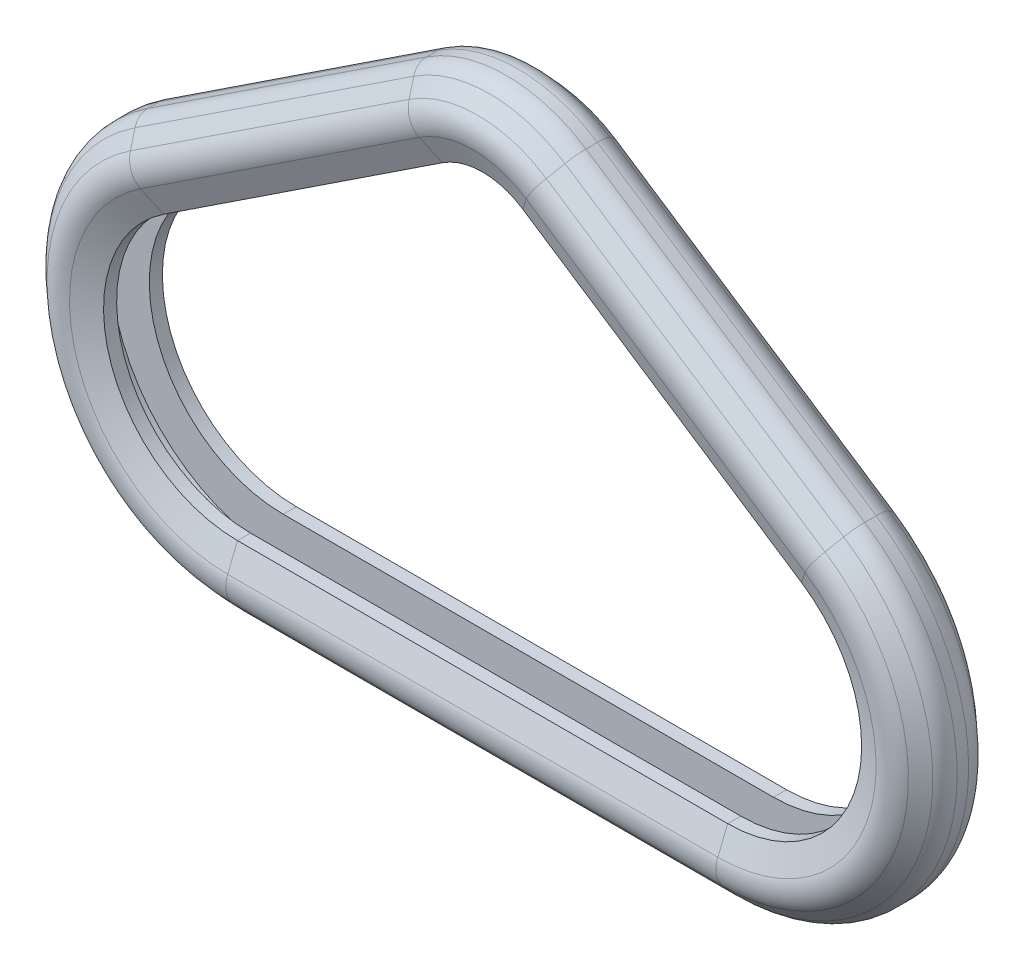
SolidWorks part; units mm, degrees
material "EPDM, dureté 60"
ref_plane "Plan de face" through (0, 0, 0) normal (0, 0, 1) x (1, 0, 0)
ref_plane "Plan de dessus" through (0, 0, 0) normal (0, 1, 0) x (1, 0, 0)
ref_plane "Plan de droite" through (0, 0, 0) normal (1, 0, 0) x (0, 0, -1)
sketch "Esquisse1" plane through (0, 0, 0) normal (0, 0, 1) x (1, 0, 0)
  line L0 (48.7921, 17.1096) -> (6.1418, 45.258)
  line L1 (-6.1418, 45.258) -> (-48.7921, 17.1096)
  line L2 (-37.5, -20.5) -> (37.5, -20.5)
  line L3 (-37.5, 0) -> (37.5, 0)
  line L4 (0, 35.9521) -> (0, 0)
  arc A0 (37.5, -20.5) -> (48.7921, 17.1096) centre (37.5, 0) ccw
  arc A1 (6.1418, 45.258) -> (-6.1418, 45.258) centre (0, 35.9521) ccw
  arc A2 (-48.7921, 17.1096) -> (-37.5, -20.5) centre (-37.5, 0) ccw
  circle B0 centre (37.5, 0) radius 20.5
  line B1 (0.1061, 35.9521) -> (0, 35.9521)
  circle B2 centre (0, 35.9521) radius 11.15
  circle B3 centre (-37.5, 0) radius 20.5
  dimension "D3" = 75
  dimension "D4" = 35.9521
sketch_block_instance "Bloc1-1"
sketch_block "Bloc1"
sketch_block_instance "Bloc2-1"
sketch_block "Bloc2" parameters "D1"=22.3
sketch_block_instance "Bloc3-1"
sketch_block "Bloc3"
other "Courroie1"
sketch "Esquisse2" plane through (0, 0, 0) normal (1, 0, 0) x (0, 0, -1)
  line L0 (-4.5, -20.5) -> (4.5, -20.5) construction
  line L1 (0, 17.1096) -> (0, -20.5) construction
  line L2 (-4.5, -20.5) -> (-2.5, -20.5)
  line L3 (4.5, -20.5) -> (2.5, -20.5)
  line L4 (-2.5, -20.5) -> (-2.5, -26.5)
  line L5 (-2.5, -26.5) -> (2.5, -26.5)
  line L6 (2.5, -26.5) -> (2.5, -20.5)
  line L7 (-12.1943, -31.5) -> (15.4694, -31.5) construction
  line L8 (-4.5, -20.5) -> (-6, -24.2081)
  line L9 (4.5, -20.5) -> (6, -24.2081)
  line L10 (-0.875, -31.5) -> (0.875, -31.5)
  line L11 (-5.2448, -28.4063) -> (-3.4588, -30.3609)
  line L12 (3.4588, -30.3609) -> (5.2448, -28.4063)
  line L13 (-2.2919, -25.7081) -> (2.2919, -25.7081) construction
  arc A0 (-5.2448, -28.4063) -> (-6, -24.2081) centre (-2.2919, -25.7081) cw
  arc A1 (-0.875, -31.5) -> (-3.4588, -30.3609) centre (-0.875, -28) cw
  arc A2 (5.2448, -28.4063) -> (6, -24.2081) centre (2.2919, -25.7081) ccw
  arc A3 (0.875, -31.5) -> (3.4588, -30.3609) centre (0.875, -28) ccw
  point P18 (-2.418, -31.5)
  point P23 (2.418, -31.5)
  dimension "D7" = 4
  dimension "D8" = 3.5
  dimension "D9" = 4
  dimension "D10" = 3.5
  dimension "D1" = 9
  dimension "D2" = 4.5
  dimension "D3" = 2
  dimension "D4" = 2
  dimension "D5" = 6
  dimension "D6" = 11
  dimension "D11" = 4
  dimension "D12" = 4
  dimension "D13" = 1.5
  dimension "D14" = 1.5
  dimension "D15" = 0.875
  dimension "D16" = 1.75
sweep "Balayage1" add profiles "Esquisse2" path "Esquisse1"
